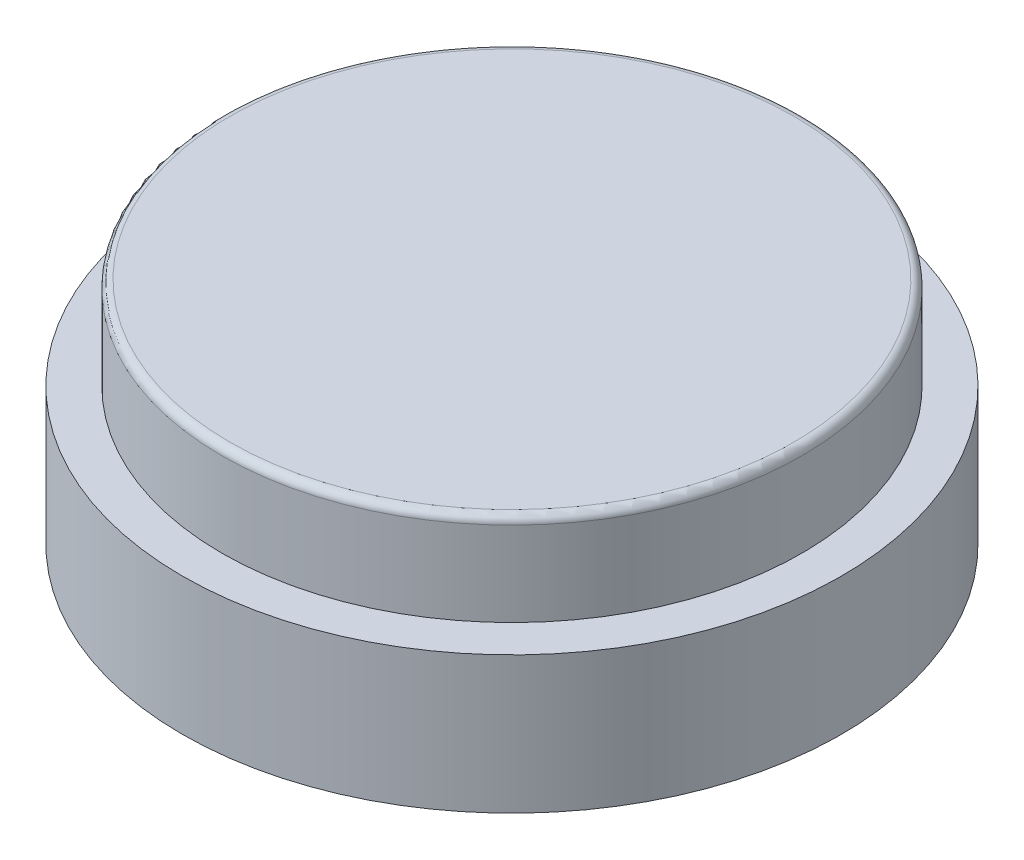
SolidWorks part; units mm, degrees
ref_plane "Front Plane" through (0, 0, 0) normal (0, 0, 1) x (1, 0, 0)
ref_plane "Top Plane" through (0, 0, 0) normal (0, 1, 0) x (1, 0, 0)
ref_plane "Right Plane" through (0, 0, 0) normal (1, 0, 0) x (0, 0, -1)
sketch "Sketch1" plane through (0, 0, 0) normal (0, 1, 0) x (1, 0, 0)
  circle A0 centre (0, 0) radius 12.5
  dimension "D1" = 25
extrude "Boss-Extrude1" add sketch "Sketch1" along normal blind 5.2
sketch "Sketch4" plane through (0, 5.2, 0) normal (0, 1, 0) x (1, 0, 0)
  circle A0 centre (0, 0) radius 11
  dimension "D1" = 22
extrude "Boss-Extrude4" add sketch "Sketch4" along normal blind 3.5
fillet "Fillet1" radius 0.3 1 edges at (0, 8.7, 11)
